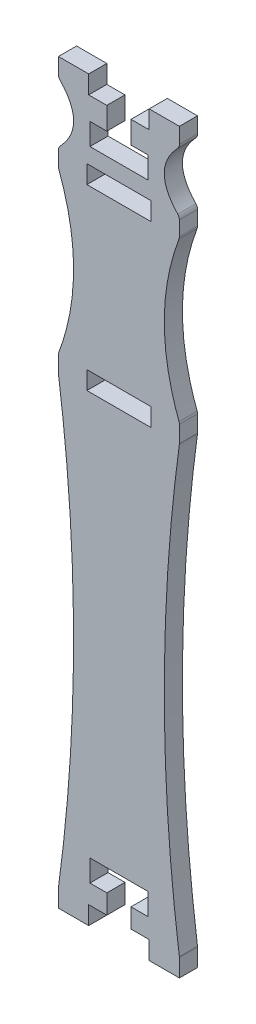
SolidWorks part; units mm, degrees
ref_plane "Alzado" through (0, 0, 0) normal (0, 0, 1) x (1, 0, 0)
ref_plane "Planta" through (0, 0, 0) normal (0, 1, 0) x (1, 0, 0)
ref_plane "Vista lateral" through (0, 0, 0) normal (1, 0, 0) x (0, 0, -1)
sketch "Croquis1" plane through (0, 0, 0) normal (0, 0, 1) x (1, 0, 0)
  line L1 (-10, 70) -> (-10, 67)
  line L2 (-7, 67) -> (-10, 67)
  line L4 (-15, 70) -> (-15, 67.4057)
  line L6 (-7, -45.5) -> (-7, -49)
  line L7 (-0.5, -42.5) -> (-9.5, -42.5)
  line L9 (-10, 70) -> (-15, 70)
  line L10 (-9.5, 60) -> (-0.5, 60)
  line L11 (-10, -52) -> (-10, -49)
  line L12 (-10, -52) -> (-15, -52)
  line L13 (-0.5, -42.5) -> (-0.5, -45.5)
  line L14 (-0.5, -45.5) -> (-3, -45.5)
  line L15 (-15, -52) -> (-15, -51.7014)
  line L16 (0, -49) -> (0, -52)
  line L17 (-0.5, 60) -> (-0.5, 63)
  line L18 (-3, -45.5) -> (-3, -49)
  line L19 (-0.5, 63) -> (-3, 63)
  line L20 (-10, 27.5) -> (-10, 24.5)
  line L21 (-3, 63) -> (-3, 67)
  line L22 (-10, 24.5) -> (0, 24.5)
  line L23 (0, 24.5) -> (0, 27.5)
  line L24 (-7, 63) -> (-7, 67)
  line L25 (-15, 27.3187) -> (-15, 24.5677)
  line L26 (-9.5, -45.5) -> (-7, -45.5)
  line L27 (-9.5, -42.5) -> (-9.5, -45.5)
  line L28 (-7, -49) -> (-10, -49)
  line L29 (-9.5, 63) -> (-7, 63)
  line L30 (-9.5, 60) -> (-9.5, 63)
  line L31 (-10, 54) -> (-10, 57)
  line L32 (-10, 54) -> (0, 54)
  line L33 (-10, 57) -> (0, 57)
  line L34 (0, 57) -> (0, 54)
  line L35 (-3, 67) -> (0, 67)
  line L36 (0, -52) -> (5, -52)
  line L37 (0, 67) -> (0, 70)
  line L38 (5, 70) -> (0, 70)
  line L39 (5, -52) -> (5, -51.7014)
  line L40 (0, 27.5) -> (-10, 27.5)
  line L42 (-15, 56.5943) -> (-15, 54.1813)
  line L43 (0, -49) -> (-3, -49)
  line L46 (-15, -49.0677) -> (-15, -51.7014)
  line L51 (5, -51.7014) -> (5, -49.0677)
  line L53 (5, 24.5677) -> (5, 27.3187)
  line L55 (5, 54.1813) -> (5, 56.5943)
  line L57 (5, 67.4057) -> (5, 70)
  arc A4 (-14.9909, -48.9331) -> (-15, -49.0677) centre (-14, -49.0677) ccw
  arc A5 (5, -49.0677) -> (4.9909, -48.9331) centre (4, -49.0677) ccw
  arc A6 (-15, 24.5677) -> (-14.9909, 24.4331) centre (-14, 24.5677) ccw
  arc A7 (4.9909, 24.4331) -> (5, 24.5677) centre (4, 24.5677) ccw
  arc A8 (-14.9371, 27.6678) -> (-15, 27.3187) centre (-14, 27.3187) ccw
  arc A9 (5, 27.3187) -> (4.9371, 27.6678) centre (4, 27.3187) ccw
  arc A10 (-14.7272, 57.2807) -> (-15, 56.5943) centre (-14, 56.5943) ccw
  arc A11 (-15, 54.1813) -> (-14.9371, 53.8322) centre (-14, 54.1813) ccw
  arc A12 (4.9371, 53.8322) -> (5, 54.1813) centre (4, 54.1813) ccw
  arc A13 (5, 56.5943) -> (4.7272, 57.2807) centre (4, 56.5943) ccw
  arc A14 (4.7272, 66.7193) -> (5, 67.4057) centre (4, 67.4057) ccw
  arc A15 (-15, 67.4057) -> (-14.7272, 66.7193) centre (-14, 67.4057) ccw
  spline S0 degree 3 poles (4.7272, 66.7193) (3.2424, 65.1462) (1.7576, 62) (3.2424, 58.8538) (4.7272, 57.2807) knots 0.028065 0.028065 0.028065 0.028065 0.5 0.971935 0.971935 0.971935 0.971935
  spline S1 degree 3 poles (-14.7272, 57.2807) (-13.2424, 58.8538) (-11.7576, 62) (-13.2424, 65.1462) (-14.7272, 66.7193) knots 0.028065 0.028065 0.028065 0.028065 0.5 0.971935 0.971935 0.971935 0.971935
  spline S2 degree 3 poles (-14.9371, 53.8322) (-13.3124, 49.4715) (-11.6876, 40.75) (-13.3124, 32.0285) (-14.9371, 27.6678) knots 0.006333 0.006333 0.006333 0.006333 0.5 0.993667 0.993667 0.993667 0.993667
  spline S3 degree 3 poles (4.9371, 53.8322) (3.3124, 49.4715) (1.6876, 40.75) (3.3124, 32.0285) (4.9371, 27.6678) knots 0.006333 0.006333 0.006333 0.006333 0.5 0.993667 0.993667 0.993667 0.993667
  spline S4 degree 3 poles (-14.9909, -48.9331) (-13.3303, -36.7054) (-11.6697, -12.25) (-13.3303, 12.2054) (-14.9909, 24.4331) knots 0.00091 0.00091 0.00091 0.00091 0.5 0.99909 0.99909 0.99909 0.99909
  spline S7 degree 3 poles (4.9909, -48.9331) (3.3303, -36.7054) (1.6697, -12.25) (3.3303, 12.2054) (4.9909, 24.4331) knots 0.00091 0.00091 0.00091 0.00091 0.5 0.99909 0.99909 0.99909 0.99909
extrude "Saliente-Extruir1" add sketch "Croquis1" along normal blind 3
sketch "Croquis2" plane through (0, 0, 3) normal (0, 0, 1) x (1, 0, 0)
  line L0 (-3, 63) -> (-3, 67) construction
  line L1 (-9.5, 60) -> (-0.5, 60)
  line L3 (-9.5, 59.7) -> (-0.5, 59.7)
  line L5 (-0.5, 63) -> (-3, 63)
  line L7 (-0.5, 63.3) -> (-3, 63.3)
  line L8 (-3, 63) -> (-3, 63.3)
  line L9 (-3, -45.5) -> (-3, -49) construction
  line L10 (-7, 63) -> (-9.5, 63)
  line L11 (-7, 63) -> (-7, 63.3)
  line L12 (-7, 63.3) -> (-9.5, 63.3)
  line L15 (-9.5, 63) -> (-9.5, 60)
  line L17 (-9.8, 63) -> (-9.8, 60)
  line L19 (-0.5, 63) -> (-0.5, 60)
  line L21 (-0.2, 63) -> (-0.2, 60)
  line L22 (-0.5, -42.5) -> (-9.5, -42.5)
  line L23 (-0.5, -42.5) -> (-0.5, -42.2)
  line L24 (-0.5, -42.2) -> (-9.5, -42.2)
  line L27 (-0.5, -45.5) -> (-0.5, -42.5)
  line L28 (-0.5, -42.5) -> (-0.2, -42.5)
  line L29 (-0.2, -45.5) -> (-0.2, -42.5)
  line L31 (-9.5, -42.5) -> (-9.5, -45.5)
  line L33 (-9.8, -42.5) -> (-9.8, -45.5)
  line L34 (-0.5, -45.5) -> (-3, -45.5)
  line L36 (-0.5, -45.8) -> (-3, -45.8)
  line L37 (-3, -45.5) -> (-3, -45.8)
  line L38 (-7, -45.5) -> (-7, -49) construction
  line L39 (-9.5, -45.5) -> (-7, -45.5)
  line L41 (-9.5, -45.8) -> (-7, -45.8)
  line L42 (-7, -45.5) -> (-7, -45.8)
  line L43 (-9.8, -42.5) -> (-9.8, -42.2)
  line L44 (-9.8, -42.2) -> (-9.5, -42.2)
  line L45 (-9.8, -45.5) -> (-9.8, -45.8)
  line L46 (-9.8, -45.8) -> (-9.5, -45.8)
  line L47 (-0.5, -45.8) -> (-0.2, -45.8)
  line L48 (-0.2, -45.8) -> (-0.2, -45.5)
  line L49 (-0.2, -42.5) -> (-0.2, -42.2)
  line L50 (-0.2, -42.2) -> (-0.5, -42.2)
  line L51 (-0.2, 60) -> (-0.2, 59.7)
  line L52 (-0.2, 59.7) -> (-0.5, 59.7)
  line L53 (-0.5, 63.3) -> (-0.2, 63.3)
  line L54 (-0.2, 63.3) -> (-0.2, 63)
  line L55 (-9.8, 60) -> (-9.8, 59.7)
  line L56 (-9.8, 59.7) -> (-9.5, 59.7)
  line L57 (-9.8, 63) -> (-9.8, 63.3)
  line L58 (-9.8, 63.3) -> (-9.5, 63.3)
  line L60 (0, 54) -> (0.3, 54)
  line L61 (0, 54) -> (0, 57)
  line L62 (0, 57) -> (0.3, 57)
  line L63 (0.3, 54) -> (0.3, 57)
  line L64 (-10, 54) -> (-10.3, 54)
  line L65 (-10, 54) -> (-10, 57)
  line L66 (-10, 57) -> (-10.3, 57)
  line L67 (-10.3, 54) -> (-10.3, 57)
  line L68 (0, 27.5) -> (0.3, 27.5)
  line L69 (0, 27.5) -> (0, 24.5)
  line L70 (0, 24.5) -> (0.3, 24.5)
  line L71 (0.3, 27.5) -> (0.3, 24.5)
  line L72 (-10, 27.5) -> (-10.3, 27.5)
  line L73 (-10, 27.5) -> (-10, 24.5)
  line L74 (-10, 24.5) -> (-10.3, 24.5)
  line L75 (-10.3, 27.5) -> (-10.3, 24.5)
extrude "Cortar-Extruir2" cut sketch "Croquis2" against normal blind 3 contours L45 L46 L41 L42 L39 L31 L22 L23 L24 L44 L43 L33 | L47 L48 L29 L28 L27 L34 L37 L36 | L49 L50 L23 L28 | L72 L75 L74 L73 | L71 L68 L69 L70 | L60 L63 L62 L61 | L67 L64 L65 L66 | L58 L57 L17 L55 L56 L3 L52 L51 L21 L54 L53 L7 L8 L5 L19 L1 L15 L10 L11 L12
